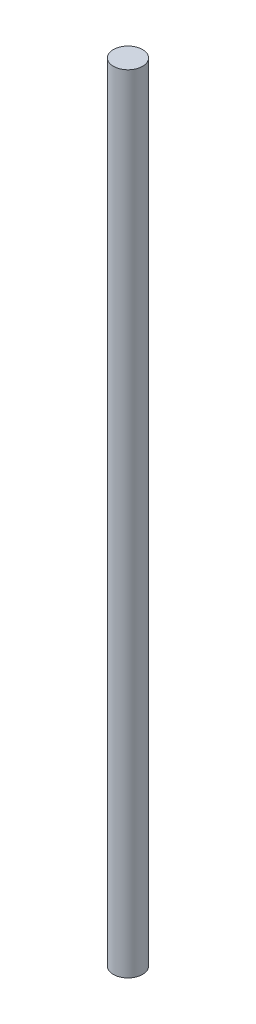
SolidWorks part; units mm, degrees
material "6061 合金"
ref_plane "前视基准面" through (0, 0, 0) normal (0, 0, 1) x (1, 0, 0)
ref_plane "上视基准面" through (0, 0, 0) normal (0, 1, 0) x (1, 0, 0)
ref_plane "右视基准面" through (0, 0, 0) normal (1, 0, 0) x (0, 0, -1)
other "Configuration Table"
sketch "草图1" plane through (0, 0, 0) normal (0, 1, 0) x (1, 0, 0)
  circle A0 centre (0, 0) radius 2
  dimension "D1" = 4
extrude "凸台-拉伸1" add sketch "草图1" along normal blind 108
